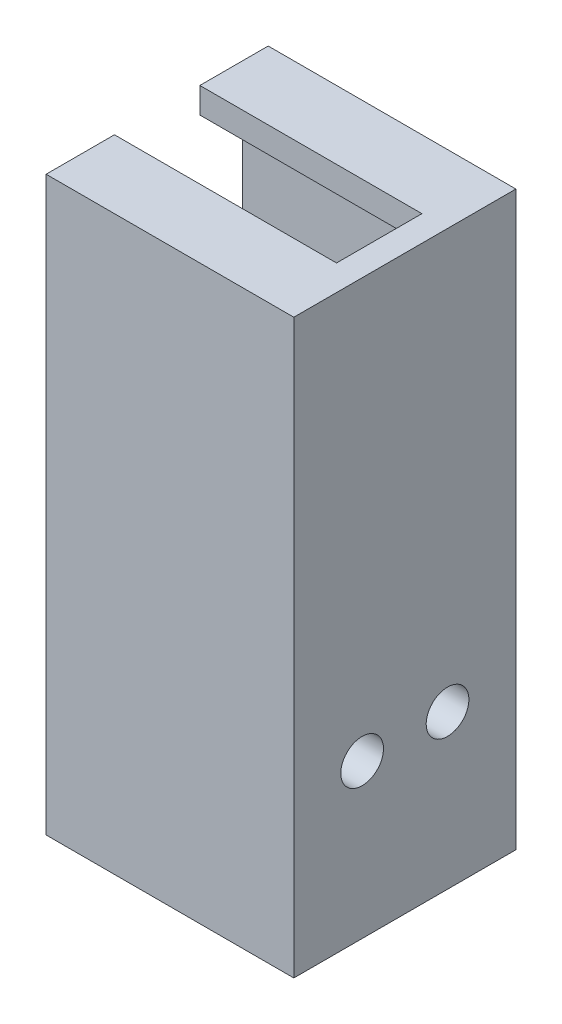
SolidWorks part; units mm, degrees
ref_plane "Front" through (0, 0, 0) normal (0, 0, 1) x (1, 0, 0)
ref_plane "Top" through (0, 0, 0) normal (0, 1, 0) x (1, 0, 0)
ref_plane "Right" through (0, 0, 0) normal (1, 0, 0) x (0, 0, -1)
sketch "Sketch1" plane through (0, 0, 0) normal (0, 0, 1) x (1, 0, 0)
  line L1 (0, 0) -> (29, 0)
  line L2 (0, 0) -> (0, 47)
  line L3 (0, 47) -> (29, 47)
  line L4 (29, 0) -> (29, 47)
  dimension "D1" = 29
  dimension "D2" = 47
extrude "Boss-Extrude1" add sketch "Sketch1" along normal blind 26
shell "Shell1" thickness 3
sketch "Sketch2" plane through (0, 0, 0) normal (-1, 0, 0) x (0, 0, 1)
  line L0 (23, 44) -> (3, 44) construction
  line L1 (8, 39.8846) -> (18, 39.8846)
  line L2 (8, 39.8846) -> (8, 48.1154)
  line L3 (8, 48.1154) -> (18, 48.1154)
  line L4 (18, 39.8846) -> (18, 48.1154)
  line L5 (8, 39.8846) -> (18, 48.1154) construction
  line L6 (8, 48.1154) -> (18, 39.8846) construction
  point P0 (13, 44)
  dimension "D1" = 10
extrude "Cut-Extrude1" cut sketch "Sketch2" against normal blind 26
sketch "Sketch3" plane through (0, 0, 0) normal (0, -1, 0) x (1, 0, 0)
  line L1 (0, 0) -> (29, 0)
  line L2 (0, 0) -> (0, 26)
  line L3 (0, 26) -> (29, 26)
  line L4 (29, 0) -> (29, 26)
extrude "Boss-Extrude2" add sketch "Sketch3" along normal blind 20
sketch "Sketch4" plane through (0, 0, 0) normal (-1, 0, 0) x (0, 0, 1)
  line L0 (8, -2) -> (18, -2) construction
  line L1 (18, -2) -> (26, -2) construction
  line L2 (26, 47) -> (26, -20) construction
  line L3 (8, -2) -> (0, -2) construction
  line L4 (0, 47) -> (0, -20) construction
  line L5 (18, -2) -> (18, 3) construction
  line L6 (23, 3) -> (3, 3) construction
  circle A0 centre (8, -2) radius 2.5
  circle A1 centre (18, -2) radius 2.5
  dimension "D1" = 5
  dimension "D2" = 5
  dimension "D3" = 10
  dimension "D4" = 5
extrude "Cut-Extrude2" cut sketch "Sketch4" against normal through all
